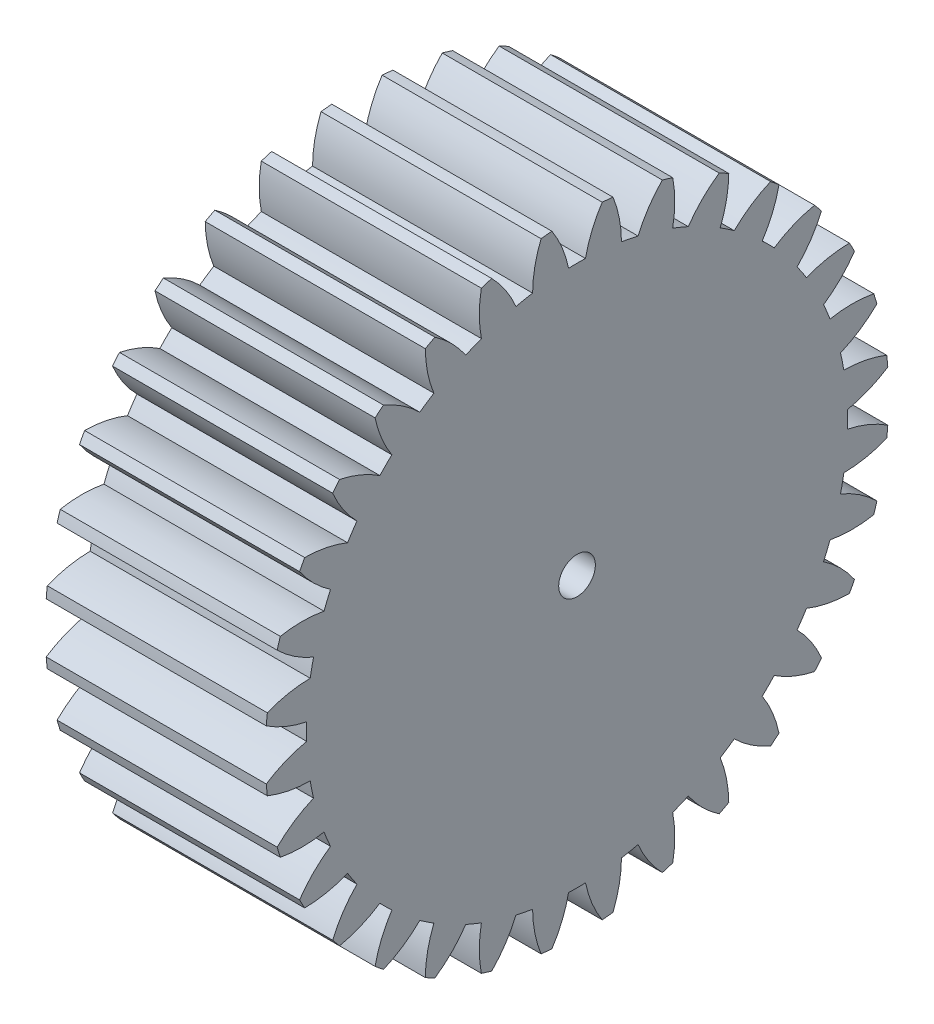
SolidWorks part; units mm, degrees
ref_plane "Plane1" through (0, 0, 0) normal (0, 0, 1) x (1, 0, 0)
ref_plane "Plane2" through (0, 0, 0) normal (0, 1, 0) x (1, 0, 0)
ref_plane "Plane3" through (0, 0, 0) normal (1, 0, 0) x (0, 0, -1)
other "Configuration Table"
sketch "HoldingSke" plane through (0, 0, 0) normal (0, 1, 0) x (1, 0, 0)
  line L0 (0, 0) -> (1.6961, -1.0598)
  line L1 (-15, 0) -> (100, 0) construction
  line L2 (0, 0) -> (-2.1039, 2.3779)
  line L3 (0, 0) -> (-11.863, 4.5341)
  line L4 (0, 0) -> (7.3237, 4.5764)
  line L5 (0, 0) -> (-46.8476, -17.4728)
  line L6 (0, 0) -> (-4.9738, -3.3558)
  line L7 (-2.1039, 2.3779) -> (8.6586, 51.2059)
  line L8 (-76.2, 54.61) -> (-76.1, 54.61)
  line L9 (-71.009, 38.7566) -> (-53.1078, 45.2721)
  line L10 (-76.2, 71.12) -> (104.1128, 71.12)
  line L11 (0, 0) -> (-6, 0)
  line L12 (-76.2, 101.6) -> (-76.181, 101.6)
  line L13 (24.9733, 27.94) -> (52.9518, 28.4284)
  line L14 (24.9733, 27.94) -> (24.9743, 27.94)
  line L15 (24.9733, 27.94) -> (100.4006, 29.5858)
  line L16 (-63.627, -0.5) -> (-12.827, -0.5)
  circle A0 centre (0, 0) radius 0.5
  circle A1 centre (0, 0) radius 7.374
  circle A2 centre (0, 0) radius 37.5
  circle A3 centre (0, 0) radius 0.5
  dimension "MHD" = 14.748
  dimension "Hub_dia" = 75
  dimension "Bore" = 1
  dimension "MBD" = 1
  dimension "Num_teeth" = 32
  dimension "Pitch" = 2
  dimension "Overall_len" = 50
  dimension "Show_teeth" = 32
  dimension "Thickness" = 6
  dimension "OAL" = 50.0001
  dimension "T_dim" = 0.1
  dimension "Ap" = 20
  dimension "H" = 19.05
  dimension "Pitch_radius" = 180.3128
  dimension "Width" = 6
  dimension "Backlash" = 0.019
  dimension "Addendum_fac" = 1
  dimension "Dedendum_fac" = 1.25
  dimension "Clearance_fac" = 0.25
  dimension "Dedendum_add" = 0.001
  dimension "Module" = 0.5
sketch "BasProSke" plane through (0, 0, 0) normal (0, 1, 0) x (1, 0, 0)
  line L0 (-10, 0) -> (60, 0) construction
  line L1 (0, 0) -> (0, 8.5)
  line L2 (0, 0) -> (6, 0)
  line L3 (6, 0) -> (6, 8.5)
  line L4 (6, 8.5) -> (0, 8.5)
  dimension "Thickness" = 6
  dimension "Diameter" = 17
revolve "Base-Revolve" add sketch "BasProSke" angle 360 about L0
sketch "TooCutSke" plane through (0, 0, 0) normal (1, 0, 0) x (0, 0, -1)
  line L1 (0, 0) -> (0, 107) construction
  line L2 (0, 0) -> (-0.4258, 7.9887) construction
  line L3 (0, 0) -> (-1.5667, 15.9069) construction
  line L4 (-0.4258, 7.9887) -> (-0.7833, 7.9534) construction
  arc A0 (0.2309, 7.3704) -> (-0.2309, 7.3704) centre (0, 0) ccw
  arc A1 (0.7014, 8.4965) -> (-0.7014, 8.4965) centre (0, 0) ccw
  circle A2 centre (0, 0) radius 8 construction
  circle A3 centre (0, 0) radius 7.5175 construction
  arc A4 (-0.2309, 7.3704) -> (-0.7014, 8.4965) centre (-3.3647, 6.7225) ccw
  arc A5 (0.7014, 8.4965) -> (0.2309, 7.3704) centre (3.3647, 6.7225) ccw
  dimension "Root_dia" = 14.748
  dimension "Overcut_dia" = 17.0508
  dimension "Pitch_dia" = 16
  dimension "Base_dia" = 15.0351
  dimension "Flank_rad" = 3.2
  dimension "Half_ang" = 5.625
  dimension "Half_CT" = 0.3593
extrude "ToothCut" cut sketch "TooCutSke" along normal through all
fillet "Breaks" [suppressed] radius 0.01
fillet "RootFillets" [suppressed] radius 0.126
pattern_circular "TeethCuts" count 32 every 11.25 about axis through (-10, 0, 0) along (1, 0, 0) of "ToothCut", "RootFillets", "Breaks"
sketch "HubNeaOneSke" plane through (0, 0, 0) normal (-1, 0, 0) x (0, 0, 1)
  circle A0 centre (0, 0) radius 7.374
  dimension "Diameter" = 14.748
extrude "HubNearOne" [suppressed] add sketch "HubNeaOneSke" along normal blind 44.0001
sketch "HubNeaBotSke" plane through (0, 0, 0) normal (-1, 0, 0) x (0, 0, 1)
  circle A0 centre (0, 0) radius 7.374
  dimension "Diameter" = 14.748
extrude "HubNearBoth" [suppressed] add sketch "HubNeaBotSke" along normal blind 22
ref_plane "FarPln" through (6, 0, 0) normal (1, 0, 0) x (0, 0, -1)
sketch "HubFarSke" plane through (6, 0, 0) normal (1, 0, 0) x (0, 0, -1)
  circle A0 centre (0, 0) radius 7.374
  dimension "Diameter" = 14.748
extrude "HubFar" [suppressed] add sketch "HubFarSke" along normal blind 22
sketch "BorSke" plane through (0, 0, 0) normal (1, 0, 0) x (0, 0, -1)
  circle A0 centre (0, 0) radius 0.5
  dimension "Diameter" = 1
extrude "Bore" cut sketch "BorSke" along normal mid plane 100.0001
sketch "KeySke" plane through (0, 0, 0) normal (1, 0, 0) x (0, 0, -1)
  line L0 (-0.05, 0) -> (-0.05, 0.6)
  line L1 (-0.05, 0.6) -> (0.05, 0.6)
  line L2 (0.05, 0.6) -> (0.05, 0)
  line L3 (0, 0) -> (0, 34) construction
  line L4 (-0.05, 0) -> (0.05, 0)
  dimension "Offset" = 0.6
  dimension "Width" = 0.1
extrude "Keyway" [suppressed] cut sketch "KeySke" along normal mid plane 100.0001
pattern_circular "Keyway2" [suppressed] count 2 every 90 about axis through (-10, 0, 0) along (1, 0, 0)
equation "' \"Module@HoldingSke\" = 6.35"
equation "' \"Num_teeth@HoldingSke\" = 12"
equation "' \"Ap@HoldingSke\" =  20"
equation "' \"Ap@HoldingSke\" = 20"
equation "' \"Width@HoldingSke\" = 0.5 * 25.4"
equation "' \"Hub_dia@HoldingSke\"= 1 * 25.4"
equation "' \"Hub_dia@HoldingSke\" = 1 * 25.4"
equation "' \"Overall_len@HoldingSke\" = 1.0 * 25.4"
equation "' \"Bore@HoldingSke\" = 0.75 * 25.4"
equation "' \"T_dim@HoldingSke\" = 0.1 * 25.4"
equation "' \"Width@KeySke\" = 0.25 * 25.4"
equation "' \"Show_teeth@HoldingSke\" = 13"
equation "' \"Backlash@HoldingSke\" = 0.009 * 25.4"
equation "' \"Addendum_fac@HoldingSke\" = 1.0"
equation "' \"Dedendum_fac@HoldingSke\" = 1.25"
equation "' \"Dedendum_add@HoldingSke\" = 0.00005 * 25.4"
equation "' \"Clearance_fac@HoldingSke\" = 0.25"
equation "\"Pitch@HoldingSke\" = 1 / \"Module@HoldingSke\""
equation "\"Overcut_dia@TooCutSke\" = (\"Num_teeth@HoldingSke\" + 2 * \"Addendum_fac@HoldingSke\") / \"Pitch@HoldingSke\" + 0.002 * 25.4"
equation "\"Pitch_dia@TooCutSke\" = \"Num_teeth@HoldingSke\" / \"Pitch@HoldingSke\""
equation "\"Base_dia@TooCutSke\" = \"Num_teeth@HoldingSke\" / \"Pitch@HoldingSke\" * cos((\"Ap@HoldingSke\"  * 3.14159265 / 180))"
equation "\"Root_dia@TooCutSke\" = (\"Num_teeth@HoldingSke\" + 2) / \"Pitch@HoldingSke\" - 2 * (\"Addendum_fac@HoldingSke\" + \"Dedendum_fac@HoldingSke\") / \"Pitch@HoldingSke\" - \"Dedendum_add@HoldingSke\" * 2"
equation "\"Half_ang@TooCutSke\" = 180 / \"Num_teeth@HoldingSke\""
equation "\"Half_CT@TooCutSke\" = \"Num_teeth@HoldingSke\" / \"Pitch@HoldingSke\" * sin((3.14159265 / 2 / \"Num_teeth@HoldingSke\")) / 2 - 7 * \"Backlash@HoldingSke\" / 4"
equation "\"Flank_rad@TooCutSke\" = \"Num_teeth@HoldingSke\" / \"Pitch@HoldingSke\" / 5"
equation "\"Radius@RootFillets\" = \"Clearance_fac@HoldingSke\" / \"Pitch@HoldingSke\" + \"Dedendum_add@HoldingSke\""
equation "\"Break_rad@Breaks\" = 0.02 / \"Pitch@HoldingSke\""
equation "\"Thickness@HoldingSke\" = \"Width@HoldingSke\""
equation "\"OAL@HoldingSke\" = \"Thickness@HoldingSke\""
equation "\"MHD@HoldingSke\" = (\"Num_teeth@HoldingSke\" + 2) / \"Pitch@HoldingSke\" - 2 * (\"Addendum_fac@HoldingSke\" + \"Dedendum_fac@HoldingSke\")  / \"Pitch@HoldingSke\" - \"Dedendum_add@HoldingSke\" * 2"
equation "\"MBD@HoldingSke\" = (\"Num_teeth@HoldingSke\" + 2) / \"Pitch@HoldingSke\" - 2 * (\"Addendum_fac@HoldingSke\" + \"Dedendum_fac@HoldingSke\")  / \"Pitch@HoldingSke\" - \"Dedendum_add@HoldingSke\" * 2 - 0.002 * 25.4"
equation "\"MHD@HoldingSke\" = ((sgn( \"MHD@HoldingSke\" - \"Hub_dia@HoldingSke\" )-1)*( \"MHD@HoldingSke\" - \"Hub_dia@HoldingSke\" ))/-2+ \"Hub_dia@HoldingSke\""
equation "\"MBD@HoldingSke\" = ((sgn( \"MBD@HoldingSke\" - \"Bore@HoldingSke\" )-1)*( \"MBD@HoldingSke\" - \"Bore@HoldingSke\" ))/-2+ \"Bore@HoldingSke\""
equation "\"OAL@HoldingSke\" = ((sgn( \"OAL@HoldingSke\" - \"Overall_len@HoldingSke\" )+1)*( \"OAL@HoldingSke\" - \"Overall_len@HoldingSke\" ))/2 + \"Overall_len@HoldingSke\" + 0.000002 * 25.4"
equation "\"Num_teeth@TeethCuts\" = int( \"Show_teeth@HoldingSke\" ) + 1"
equation "\"Num_teeth@TeethCuts\" = ((sgn( \"Num_teeth@TeethCuts\" - \"Num_teeth@HoldingSke\" )-1)*( \"Num_teeth@TeethCuts\" - \"Num_teeth@HoldingSke\" ))/-2+ \"Num_teeth@HoldingSke\""
equation "\"Num_teeth@TeethCuts\" = ((sgn( \"Num_teeth@TeethCuts\" - 2.0)+1)*( \"Num_teeth@TeethCuts\" - 2.0))/2 +2.0"
equation "\"Angle@TeethCuts\" = 360.0 / \"Num_teeth@HoldingSke\""
equation "\"Diameter@BasProSke\" = (\"Num_teeth@HoldingSke\" + 2 * \"Addendum_fac@HoldingSke\") / \"Pitch@HoldingSke\""
equation "\"Thickness@BasProSke\"  = \"Thickness@HoldingSke\""
equation "' \"Fillet_rad@BasProSke\" =  \"Thickness@HoldingSke\" * 0.05"
equation "' \"Fillet_rad@BasProSke\" = \"Thickness@HoldingSke\" * 0.05"
equation "\"MHD@HoldingSke\" = ((sgn( \"MHD@HoldingSke\" - \"Root_dia@TooCutSke\" )-1)*( \"MHD@HoldingSke\" - \"Root_dia@TooCutSke\" ))/-2+ \"Root_dia@TooCutSke\""
equation "\"Diameter@HubNeaOneSke\" = \"MHD@HoldingSke\""
equation "\"Length@HubNearOne\" = \"OAL@HoldingSke\" - \"Thickness@BasProSke\""
equation "\"Diameter@HubNeaBotSke\" = \"MHD@HoldingSke\""
equation "\"Length@HubNearBoth\" = ( \"OAL@HoldingSke\" - \"Thickness@BasProSke\" ) / 2.0"
equation "\"Thickness@FarPln\" = \"Thickness@BasProSke\""
equation "\"Diameter@HubFarSke\" = \"MHD@HoldingSke\""
equation "\"Length@HubFar\" = ( \"OAL@HoldingSke\" - \"Thickness@BasProSke\" ) / 2.0"
equation "\"Diameter@BorSke\" = \"MBD@HoldingSke\""
equation "\"D1@Bore\" = \"OAL@HoldingSke\" * 2.0"
equation "\"D1@Keyway\" = \"OAL@HoldingSke\" * 2.0"
equation "\"Offset@KeySke\" = \"T_dim@HoldingSke\" + \"MBD@HoldingSke\" / 2.0"
